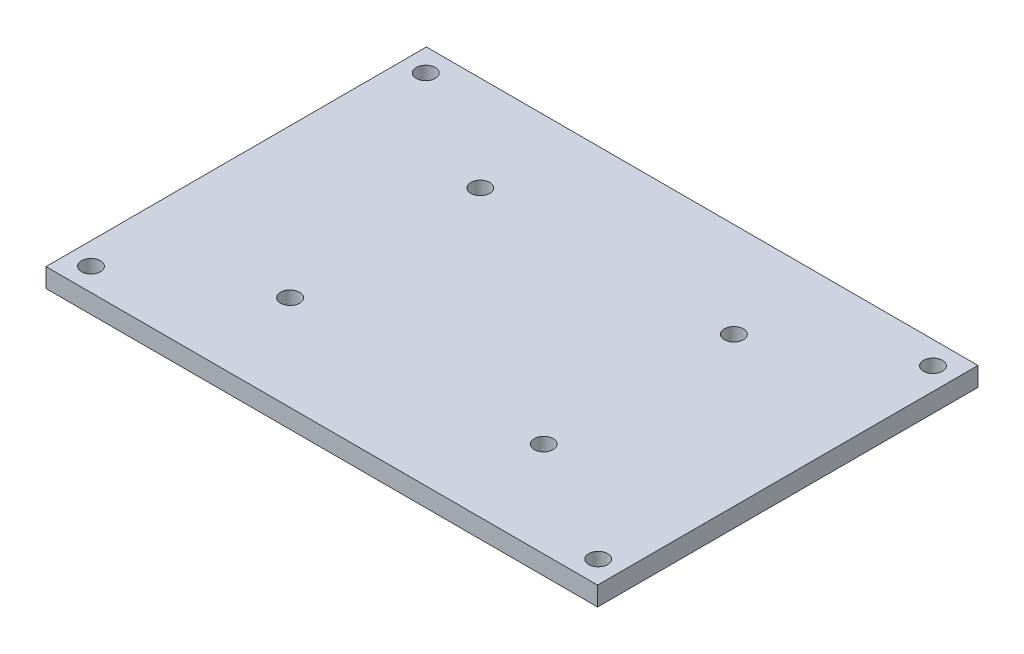
SolidWorks part; units mm, degrees
ref_plane "前视基准面" through (0, 0, 0) normal (0, 0, 1) x (1, 0, 0)
ref_plane "上视基准面" through (0, 0, 0) normal (0, 1, 0) x (1, 0, 0)
ref_plane "右视基准面" through (0, 0, 0) normal (1, 0, 0) x (0, 0, -1)
other "Configuration Table"
sketch "草图1" plane through (0, 0, 0) normal (0, 1, 0) x (1, 0, 0)
  line L1 (-43.5, -30) -> (43.5, -30)
  line L2 (-43.5, -30) -> (-43.5, 30)
  line L3 (-43.5, 30) -> (43.5, 30)
  line L4 (43.5, -30) -> (43.5, 30)
  line L5 (-43.5, -30) -> (43.5, 30) construction
  line L6 (-43.5, 30) -> (43.5, -30) construction
  point P0 (0, 0)
  dimension "D1" = 87
  dimension "D2" = 60
extrude "凸台-拉伸1" add sketch "草图1" along normal blind 3
sketch "草图2" plane through (0, 3, 0) normal (0, 1, 0) x (1, 0, 0)
  line L1 (-40, -26.4) -> (40, -26.4) construction
  line L2 (-40, -26.4) -> (-40, 26.4) construction
  line L3 (-40, 26.4) -> (40, 26.4) construction
  line L4 (40, -26.4) -> (40, 26.4) construction
  line L5 (-40, -26.4) -> (40, 26.4) construction
  line L6 (-40, 26.4) -> (40, -26.4) construction
  circle A0 centre (-40, 26.4) radius 1.5
  circle A1 centre (40, 26.4) radius 1.5
  circle A2 centre (40, -26.4) radius 1.5
  circle A3 centre (-40, -26.4) radius 1.5
  point P0 (0, 0)
  dimension "D3" = 3
  dimension "D1" = 80
  dimension "D2" = 52.8
extrude "切除-拉伸1" cut sketch "草图2" against normal through all
sketch "草图3" plane through (0, 3, 0) normal (0, 1, 0) x (1, 0, 0)
  line L1 (-20, -15) -> (20, -15) construction
  line L2 (-20, -15) -> (-20, 15) construction
  line L3 (-20, 15) -> (20, 15) construction
  line L4 (20, -15) -> (20, 15) construction
  line L5 (-20, -15) -> (20, 15) construction
  line L6 (-20, 15) -> (20, -15) construction
  circle A0 centre (20, 15) radius 1.5
  circle A1 centre (20, -15) radius 1.5
  circle A2 centre (-20, 15) radius 1.5
  circle A3 centre (-20, -15) radius 1.5
  point P0 (0, 0)
  dimension "D3" = 3
  dimension "D1" = 30
  dimension "D2" = 40
extrude "切除-拉伸2" cut sketch "草图3" against normal through all
